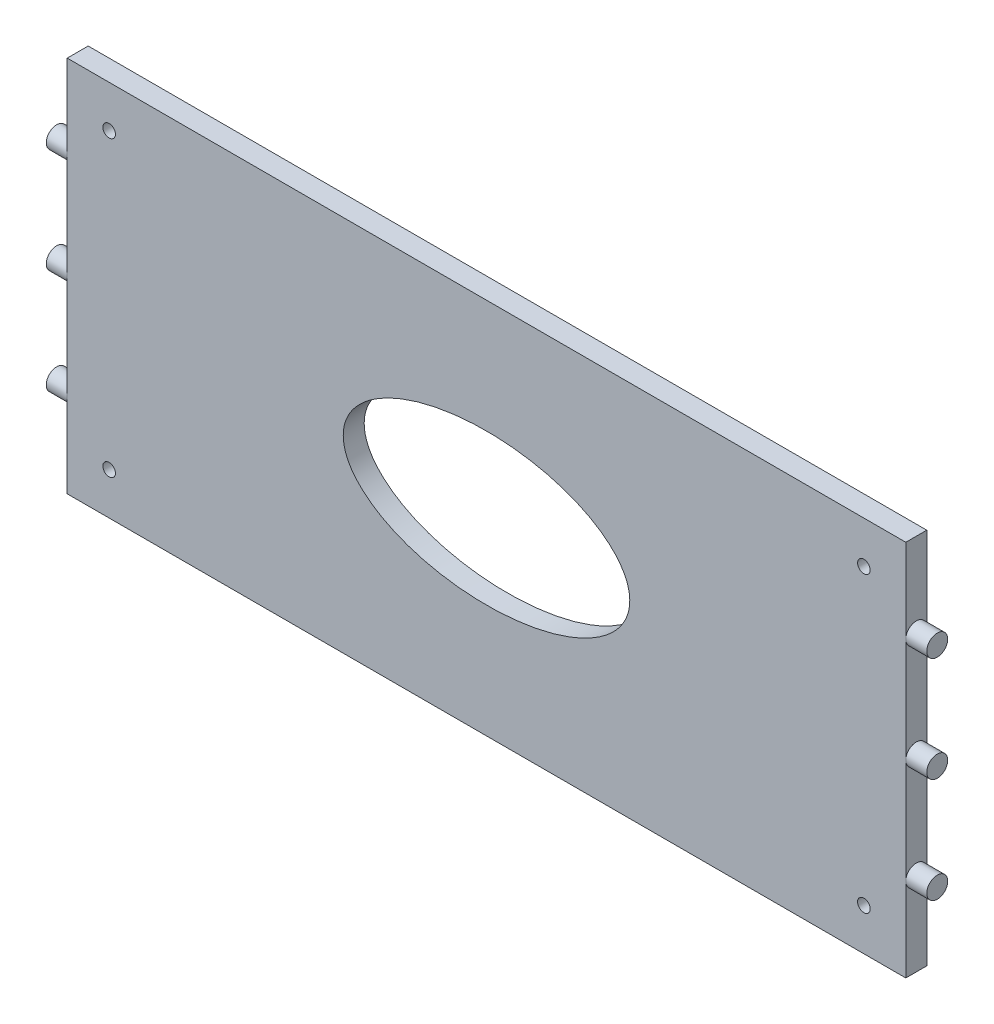
SolidWorks part; units mm, degrees
ref_plane "Front Plane" through (0, 0, 0) normal (0, 0, 1) x (1, 0, 0)
ref_plane "Top Plane" through (0, 0, 0) normal (0, 1, 0) x (1, 0, 0)
ref_plane "Right Plane" through (0, 0, 0) normal (1, 0, 0) x (0, 0, -1)
sketch "Sketch1" plane through (0, 0, 0) normal (0, 0, 1) x (1, 0, 0)
  line L1 (-100, -45) -> (100, -45)
  line L2 (-100, -45) -> (-100, 45)
  line L3 (-100, 45) -> (100, 45)
  line L4 (100, -45) -> (100, 45)
  line L5 (-100, -45) -> (100, 45) construction
  line L6 (-100, 45) -> (100, -45) construction
  point P0 (0, 0)
  dimension "D1" = 200
  dimension "D2" = 90
extrude "Boss-Extrude1" add sketch "Sketch1" along normal blind 5
sketch "Sketch2" plane through (100, 0, 0) normal (1, 0, 0) x (0, 0, -1)
  circle A0 centre (-2.5, 0) radius 2.5
  circle A1 centre (-2.5, 25) radius 2.5
  circle A2 centre (-2.5, 0) radius 2.5
  circle A3 centre (-2.5, -25) radius 2.5
  dimension "D1" = 5
  dimension "D2" = 2
  dimension "D3" = 2
extrude "Boss-Extrude2" add sketch "Sketch2" along normal blind 5 contours A1 | A0 | A3
mirror "Mirror1" about plane through (0, 0, 0) normal (1, 0, 0) of "Boss-Extrude2"
sketch "Sketch3" plane through (0, 0, 0) normal (0, 0, -1) x (-1, 0, 0)
  line L0 (-100, 45) -> (100, 45) construction
  line L1 (-100, 25) -> (-100, 45) construction
  line L2 (2.75, 0) -> (-2.75, 0) construction
  line L3 (0, 2.75) -> (0, -2.75) construction
  circle A0 centre (-90, 35) radius 1.5
  circle A1 centre (-90, -35) radius 1.5
  circle A2 centre (90, -35) radius 1.5
  circle A3 centre (90, 35) radius 1.5
  ellipse E0 centre (0, 0) end of major axis (34.1714, 0) minor radius 17.9909
  dimension "D3" = 3
  dimension "D1" = 10
  dimension "D2" = 10
extrude "Cut-Extrude1" cut sketch "Sketch3" against normal blind 5
